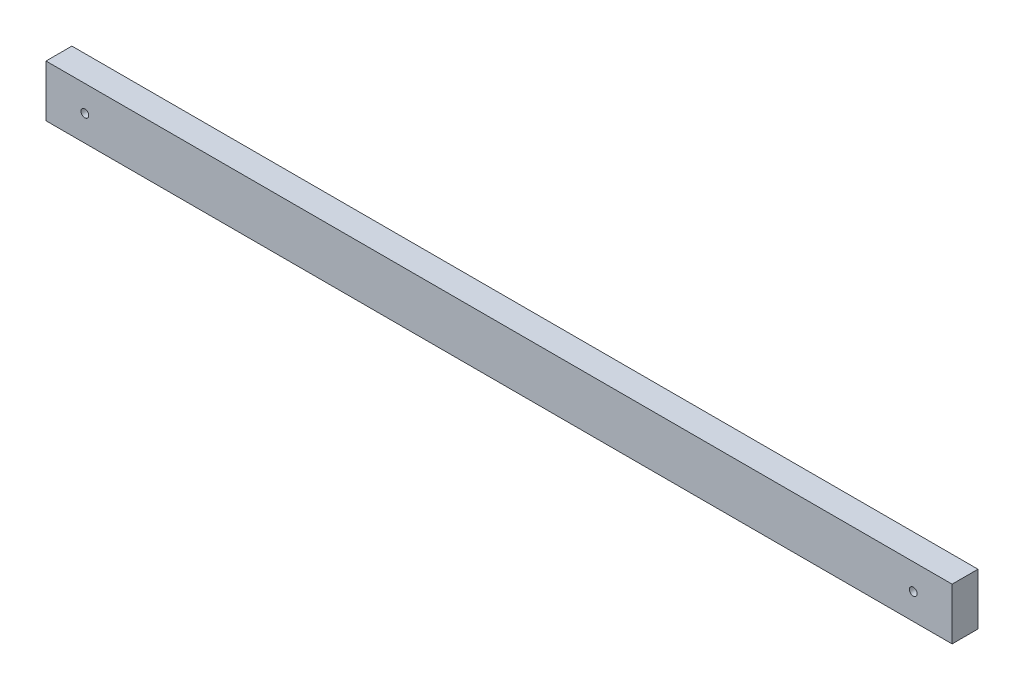
SolidWorks part; units mm, degrees
ref_plane "Front Plane" through (0, 0, 0) normal (0, 0, 1) x (1, 0, 0)
ref_plane "Top Plane" through (0, 0, 0) normal (0, 1, 0) x (1, 0, 0)
ref_plane "Right Plane" through (0, 0, 0) normal (1, 0, 0) x (0, 0, -1)
sketch "Sketch1" plane through (0, 0, 0) normal (0, 0, 1) x (1, 0, 0)
  line L1 (175, -10) -> (-175, -10)
  line L2 (175, -10) -> (175, 10)
  line L3 (175, 10) -> (-175, 10)
  line L4 (-175, -10) -> (-175, 10)
  line L5 (175, -10) -> (-175, 10) construction
  line L6 (175, 10) -> (-175, -10) construction
  point P0 (0, 0)
  dimension "D1" = 350
  dimension "D2" = 20
extrude "Boss-Extrude1" add sketch "Sketch1" along normal blind 10
sketch "Sketch2" plane through (0, 0, 10) normal (0, 0, 1) x (1, 0, 0)
  line L0 (-175, 0) -> (175, 0) construction
  line L1 (-175, 10) -> (-175, -10) construction
  line L2 (175, -10) -> (175, 10) construction
  line L3 (0, 0) -> (0, 10) construction
  line L4 (175, 10) -> (-175, 10) construction
  circle A0 centre (-160, 0) radius 1.5
  circle A1 centre (160, 0) radius 1.5
  dimension "D1" = 3
  dimension "D2" = 160
extrude "Cut-Extrude1" cut sketch "Sketch2" against normal through all
